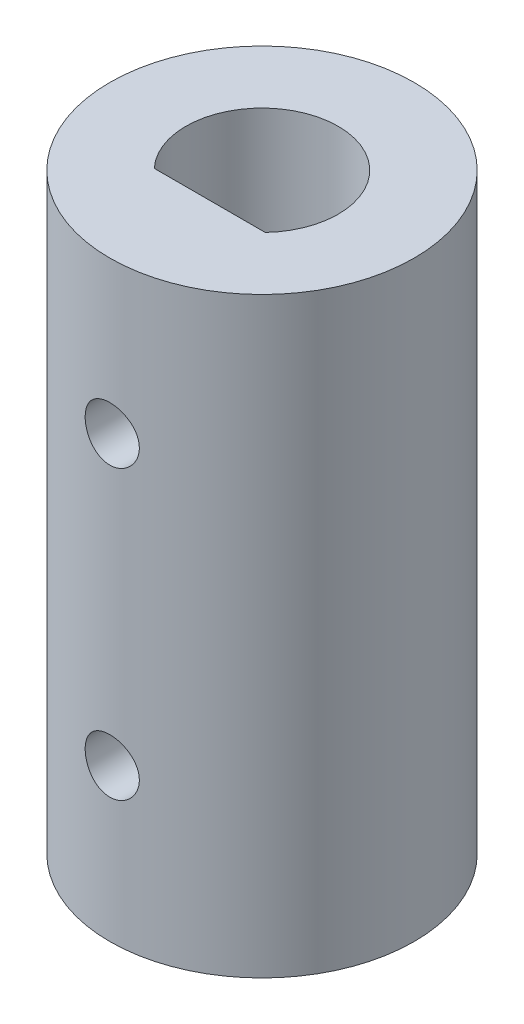
SolidWorks part; units mm, degrees
material "Brass"
ref_plane "Front Plane" through (0, 0, 0) normal (0, 0, 1) x (1, 0, 0)
ref_plane "Top Plane" through (0, 0, 0) normal (0, 1, 0) x (1, 0, 0)
ref_plane "Right Plane" through (0, 0, 0) normal (1, 0, 0) x (0, 0, -1)
sketch "Sketch1" plane through (0, 0, 0) normal (0, 1, 0) x (1, 0, 0)
  line L0 (0, -4.2603) -> (0, -3.2603) construction
  line L1 (-2.7424, -3.2603) -> (2.7424, -3.2603)
  arc A0 (2.7424, -3.2603) -> (-2.7424, -3.2603) centre (0, 0) ccw
  circle A1 centre (0, 0) radius 6.35
  dimension "D1" = 8.5207
  dimension "D2" = 12.7
  dimension "D3" = 1
extrude "Boss-Extrude1" add sketch "Sketch1" along normal blind 12.35
sketch "Sketch4" plane through (0, 12.35, 0) normal (0, 1, 0) x (1, 0, 0)
  line L0 (0, -3.18) -> (0, -2.18) construction
  line L1 (-2.3152, -2.18) -> (2.3152, -2.18)
  arc A0 (2.3152, -2.18) -> (-2.3152, -2.18) centre (0, 0) ccw
  circle A1 centre (0, 0) radius 6.35
  dimension "D1" = 12.7
  dimension "D2" = 6.36
  dimension "D3" = 1
extrude "Boss-Extrude2" add sketch "Sketch4" along normal blind 12.35
sketch "Sketch5" plane through (0, 0, 3.2603) normal (0, 0, -1) x (-1, 0, 0)
  line L0 (3.18, 24.7) -> (-3.18, 24.7) construction
  line L1 (-6.35, 12.35) -> (6.35, 12.35) construction
  line L2 (-6.35, 24.7) -> (-6.35, 0) construction
  line L3 (6.35, 0) -> (6.35, 24.7) construction
  line L4 (0, 24.7) -> (0, 0) construction
  circle A0 centre (0, 18.35) radius 1.13
  circle A1 centre (0, 6.35) radius 1.13
  point P12 (0, 0)
  dimension "D2" = 2.26
  dimension "D1" = 6.35
extrude "Cut-Extrude2" cut sketch "Sketch5" against normal through all
